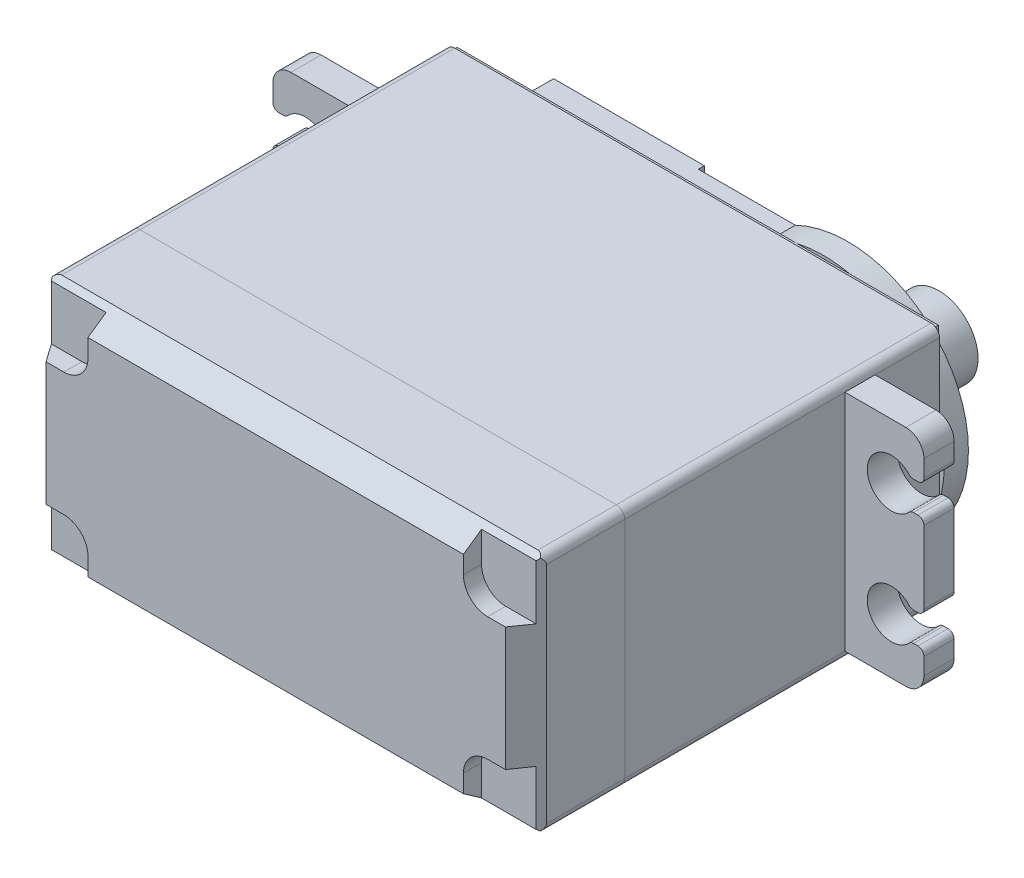
SolidWorks part; units mm, degrees
ref_plane "Front Plane" through (0, 0, 0) normal (0, 0, 1) x (1, 0, 0)
ref_plane "Top Plane" through (0, 0, 0) normal (0, 1, 0) x (1, 0, 0)
ref_plane "Right Plane" through (0, 0, 0) normal (1, 0, 0) x (0, 0, -1)
sketch "Sketch1" plane through (0, 0, 0) normal (0, 0, 1) x (1, 0, 0)
  line L1 (-20.45, 10) -> (20.45, 10)
  line L2 (-20.45, 10) -> (-20.45, -10)
  line L3 (-20.45, -10) -> (20.45, -10)
  line L4 (20.45, 10) -> (20.45, -10)
  line L5 (-20.45, 10) -> (20.45, -10) construction
  line L6 (-20.45, -10) -> (20.45, 10) construction
  point P0 (0, 0)
  dimension "D1" = 20
  dimension "D2" = 40.9
extrude "Boss-Extrude1" add sketch "Sketch1" along normal blind 19.3
sketch "Sketch4" plane through (0, 0, 0) normal (0, 0, -1) x (-1, 0, 0)
  line L4 (-20.45, 10) -> (-20.45, -10)
  line L5 (-20.45, -10) -> (20.45, -10)
  line L6 (20.45, -10) -> (20.45, 10)
  line L7 (20.45, 10) -> (-20.45, 10)
  line L8 (-20.45, 10) -> (-20.45, -10)
  line L9 (-20.45, -10) -> (20.45, -10)
  line L10 (20.45, -10) -> (20.45, 10)
  line L11 (20.45, 10) -> (-20.45, 10)
  dimension "D1" = 0
extrude "Boss-Extrude2" add sketch "Sketch4" along normal blind 6.8 separate body
sketch "Sketch5" plane through (0, 0, 19.3) normal (0, 0, 1) x (1, 0, 0)
  line L4 (20.45, -10) -> (20.45, 10)
  line L5 (20.45, 10) -> (-20.45, 10)
  line L6 (-20.45, 10) -> (-20.45, -10)
  line L7 (-20.45, -10) -> (20.45, -10)
  line L8 (20.45, -10) -> (20.45, 10)
  line L9 (20.45, 10) -> (-20.45, 10)
  line L10 (-20.45, 10) -> (-20.45, -10)
  line L11 (-20.45, -10) -> (20.45, -10)
  dimension "D1" = 0
extrude "Boss-Extrude3" add sketch "Sketch5" along normal blind 8.5 separate body
chamfer "Chamfer1" distance 2 angle 35 4 edges at (-20.45, 0, 27.8) (0, 10, 27.8) (20.45, 0, 27.8) (0, -10, 27.8)
sketch "Sketch7" plane through (0, 0, 27.8) normal (0, 0, 1) x (1, 0, 0)
  line L0 (0, 0) -> (0, 10) construction
  line L1 (-20.45, 10) -> (-15.57, 10)
  line L2 (-20.45, 10) -> (-20.45, 5.12)
  line L3 (-20.45, 5.12) -> (-17.57, 5.12)
  line L4 (-15.57, 10) -> (-15.57, 7.12)
  line L5 (-20.45, 10) -> (20.45, 10) construction
  line L6 (0, 0) -> (-20.45, 0) construction
  line L7 (-20.45, -10) -> (-20.45, 10) construction
  line L8 (15.57, 10) -> (15.57, 7.12)
  line L9 (20.45, 5.12) -> (17.57, 5.12)
  line L10 (20.45, 10) -> (20.45, 5.12)
  line L11 (20.45, 10) -> (15.57, 10)
  line L12 (-15.57, -10) -> (-15.57, -7.12)
  line L13 (-20.45, -5.12) -> (-17.57, -5.12)
  line L14 (-20.45, -10) -> (-20.45, -5.12)
  line L15 (-20.45, -10) -> (-15.57, -10)
  line L16 (0, 0) -> (20.45, 0) construction
  line L17 (20.45, 10) -> (20.45, -10) construction
  line L18 (20.45, -10) -> (15.57, -10)
  line L19 (20.45, -10) -> (20.45, -5.12)
  line L20 (20.45, -5.12) -> (17.57, -5.12)
  line L21 (15.57, -10) -> (15.57, -7.12)
  arc A0 (-17.57, 5.12) -> (-15.57, 7.12) centre (-17.57, 7.12) ccw
  arc A1 (17.57, 5.12) -> (15.57, 7.12) centre (17.57, 7.12) cw
  arc A2 (-17.57, -5.12) -> (-15.57, -7.12) centre (-17.57, -7.12) cw
  arc A3 (17.57, -5.12) -> (15.57, -7.12) centre (17.57, -7.12) ccw
  dimension "D3" = 2
  dimension "D1" = 4.88
  dimension "D2" = 4.88
extrude "Cut-Extrude1" cut sketch "Sketch7" against normal blind 1.5
sketch "Sketch8" plane through (0, 0, -6.8) normal (0, 0, -1) x (-1, 0, 0)
  line L0 (20.45, 10) -> (-20.45, 10) construction
  line L1 (-19.95, 9.75) -> (19.95, 9.75)
  line L2 (-19.95, 9.75) -> (-19.95, -9.75)
  line L3 (-19.95, -9.75) -> (19.95, -9.75)
  line L4 (19.95, 9.75) -> (19.95, -9.75)
  line L5 (-19.95, 9.75) -> (19.95, -9.75) construction
  line L6 (-19.95, -9.75) -> (19.95, 9.75) construction
  line L7 (20.45, -10) -> (20.45, 10) construction
  point P0 (0, 0)
  dimension "D1" = 0.25
  dimension "D2" = 0.5
extrude "Boss-Extrude4" add sketch "Sketch8" along normal blind 0.4
sketch "Sketch9" plane through (0, 0, -7.2) normal (0, 0, -1) x (-1, 0, 0)
  line L0 (-20.45, 0) -> (20.45, 0) construction
  line L1 (-20.45, 10) -> (-20.45, -10) construction
  line L2 (20.45, -10) -> (20.45, 10) construction
  line L3 (20.45, 10) -> (-20.45, 10) construction
  line L4 (-6.09, 10) -> (-6.09, -10) construction
  line L5 (-20.45, -10) -> (20.45, -10) construction
  line L6 (-6.09, 8.9995) -> (14.45, 8.9995)
  line L7 (14.45, 3) -> (14.45, 8.9995)
  line L8 (14.45, -3) -> (14.45, -8.9995)
  line L9 (-6.09, -8.9995) -> (14.45, -8.9995)
  arc A0 (-6.09, 8.9995) -> (-6.09, -8.9995) centre (-10.45, 0) ccw
  arc A1 (14.45, -3) -> (14.45, 3) centre (14.45, 0) ccw
  point P20 (17.45, 0)
  dimension "D1" = 14.36
  dimension "D2" = 6
  dimension "D3" = 3
extrude "Boss-Extrude5" add sketch "Sketch9" along normal blind 2
sketch "Sketch11" plane through (0, 0, -9.2) normal (0, 0, -1) x (-1, 0, 0)
  circle A0 centre (-10.9994, 0) radius 6.5
  dimension "D1" = 13
extrude "Boss-Extrude6" add sketch "Sketch11" along normal blind 1.5
sketch "Sketch12" plane through (0, 0, -10.7) normal (0, 0, -1) x (-1, 0, 0)
  circle A0 centre (-10.9994, 0) radius 5.5
  dimension "D1" = 11
extrude "Boss-Extrude7" add sketch "Sketch12" along normal blind 0.5
sketch "Sketch13" plane through (0, 0, -11.2) normal (0, 0, -1) x (-1, 0, 0)
  circle A0 centre (-10.9994, 0) radius 3.25
  dimension "D1" = 6.5
extrude "Boss-Extrude8" add sketch "Sketch13" along normal blind 5
sketch "Sketch14" plane through (0, 0, -9.2) normal (0, 0, -1) x (-1, 0, 0)
  line L0 (-6.09, -8.9995) -> (14.45, -8.9995) construction
  line L1 (14.45, 8.9995) -> (1.95, 8.9995)
  line L2 (14.45, 8.9995) -> (14.45, -8.9995)
  line L3 (14.45, -8.9995) -> (1.95, -8.9995)
  line L4 (1.95, 8.9995) -> (1.95, -8.9995)
  line L5 (13.45, 7.9995) -> (2.95, 7.9995)
  line L6 (2.95, 7.9995) -> (2.95, -7.9995)
  line L7 (13.45, -7.9995) -> (2.95, -7.9995)
  line L8 (13.45, 7.9995) -> (13.45, -7.9995)
  arc A0 (1.95, 1.75) -> (1.95, -1.75) centre (1.95, 0) ccw
  dimension "D3" = 3.5
  dimension "D1" = 12.5
  dimension "D2" = 1
extrude "Boss-Extrude9" add sketch "Sketch14" along normal blind 0.5 contours L4 A0 | L8 L7 L6 L5
fillet "Fillet1" radius 0.7 4 edges at (20.45, -10, 9.65) (-20.45, -10, 9.65) (-20.45, 10, 9.65) (20.45, 10, 9.65)
fillet "Fillet2" radius 0.7 4 edges at (-20.45, 10, -3.4) (-20.45, -10, -3.4) (20.45, -10, -3.4) (20.45, 10, -3.4)
fillet "Fillet3" radius 0.7 4 edges at (-20.45, -10, 22.55) (-20.45, 10, 22.55) (20.45, -10, 22.55) (20.45, 10, 22.55)
sketch "Sketch15" plane through (0, 0, -7.2) normal (0, 0, -1) x (-1, 0, 0)
  line L0 (20.45, 9.3) -> (25.5, 9.3)
  line L1 (27, 7.8) -> (27, 6.4)
  line L2 (0.2, 0) -> (32.799, 0) construction
  line L3 (20.45, -9.3) -> (20.45, 9.3) construction
  line L4 (0, 9.75) -> (0, -9.75) construction
  line L5 (19.95, 9.75) -> (-19.95, 9.75) construction
  line L6 (-19.95, -9.75) -> (19.95, -9.75) construction
  line L7 (25.9, 9.3) -> (25.9, -9.3) construction
  line L8 (26.133, 5.9) -> (26.5, 5.9)
  line L9 (26.133, 3.5) -> (26.5, 3.5)
  line L10 (27, 3) -> (27, -3)
  line L11 (26.133, -3.5) -> (26.5, -3.5)
  line L12 (26.133, -5.9) -> (26.5, -5.9)
  line L13 (27, -7.8) -> (27, -6.4)
  line L14 (20.45, -9.3) -> (25.5, -9.3)
  line L15 (20.45, 9.3) -> (20.45, -9.3)
  arc A0 (1.95, 1.75) -> (1.95, -1.75) centre (1.95, 0) ccw construction
  arc A1 (25.7664, 6.06) -> (25.7664, 3.34) centre (24.3, 4.7) ccw
  arc A2 (26.5, 3.5) -> (27, 3) centre (26.5, 3) cw
  arc A3 (25.7664, 3.34) -> (26.133, 3.5) centre (26.133, 3) cw
  arc A4 (26.5, 5.9) -> (27, 6.4) centre (26.5, 6.4) ccw
  arc A5 (25.7664, 6.06) -> (26.133, 5.9) centre (26.133, 6.4) ccw
  arc A6 (25.5, 9.3) -> (27, 7.8) centre (25.5, 7.8) cw
  arc A7 (25.5, -9.3) -> (27, -7.8) centre (25.5, -7.8) ccw
  arc A8 (25.7664, -6.06) -> (26.133, -5.9) centre (26.133, -6.4) cw
  arc A9 (26.5, -5.9) -> (27, -6.4) centre (26.5, -6.4) cw
  arc A10 (25.7664, -3.34) -> (26.133, -3.5) centre (26.133, -3) ccw
  arc A11 (26.5, -3.5) -> (27, -3) centre (26.5, -3) ccw
  arc A12 (25.7664, -6.06) -> (25.7664, -3.34) centre (24.3, -4.7) cw
  point P27 (27, 3.5)
  point P30 (25.9, 3.5)
  point P35 (25.9, 5.9)
  point P39 (25.9, 0)
  point P55 (27, 0)
  point P56 (25.9, -5.9)
  point P57 (25.9, -3.5)
  point P58 (27, -3.5)
  dimension "D2" = 4
  dimension "D6" = 0.5
  dimension "D7" = 1.5
  dimension "D1" = 6.55
  dimension "D3" = 4.7
  dimension "D4" = 24.3
  dimension "D5" = 1.1
extrude "Boss-Extrude10" add sketch "Sketch15" against normal blind 2.5 from offset 5.74 offset against normal yes
mirror "Mirror1" about plane through (0, 0, 0) normal (1, 0, 0) of "Boss-Extrude10"
equation "\"5.740.00mm\"=0"
